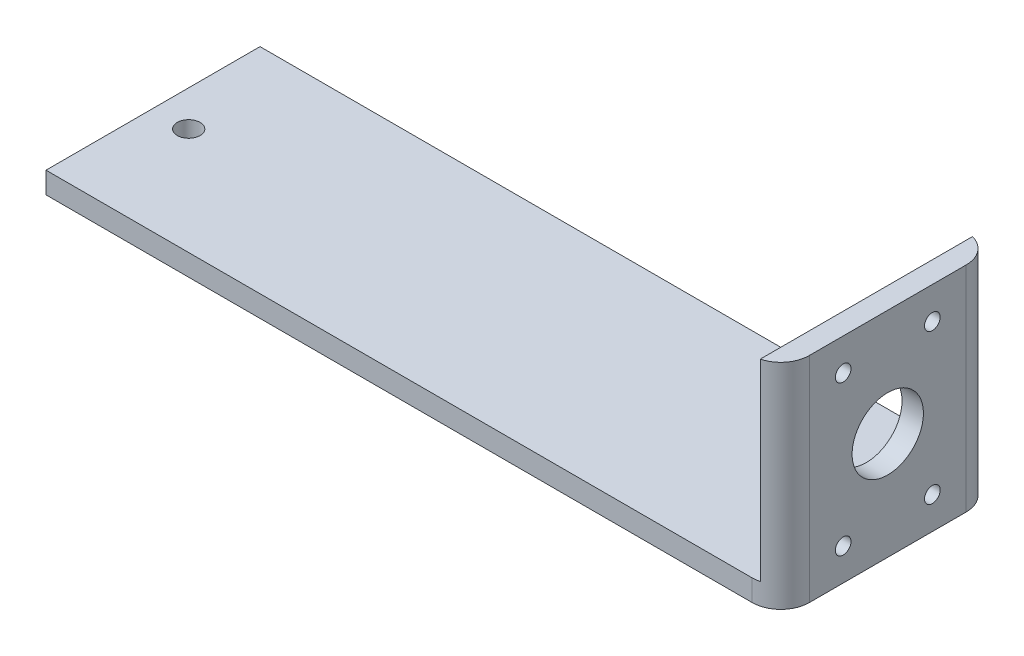
SolidWorks part; units mm, degrees
ref_plane "Front Plane" through (0, 0, 0) normal (0, 0, 1) x (1, 0, 0)
ref_plane "Top Plane" through (0, 0, 0) normal (0, 1, 0) x (1, 0, 0)
ref_plane "Right Plane" through (0, 0, 0) normal (1, 0, 0) x (0, 0, -1)
sketch "Sketch1" plane through (0, 0, 0) normal (0, 1, 0) x (1, 0, 0)
  line L1 (-50, 15) -> (50, 15)
  line L2 (-50, 15) -> (-50, -15)
  line L3 (-50, -15) -> (50, -15)
  line L4 (50, 15) -> (50, -15)
  line L5 (-50, 15) -> (50, -15) construction
  line L6 (-50, -15) -> (50, 15) construction
  point P0 (0, 0)
  dimension "D1" = 100
  dimension "D2" = 30
extrude "Boss-Extrude1" add sketch "Sketch1" along normal blind 3
sketch "Sketch2" plane through (0, 3, 0) normal (0, 1, 0) x (1, 0, 0)
  line L0 (0, -1.65) -> (0, 1.65) construction
  circle A0 centre (45, 0) radius 1.6
  circle A1 centre (-45, 0) radius 1.6
  dimension "D1" = 45
  dimension "D2" = 3.2
extrude "Cut-Extrude1" cut sketch "Sketch2" against normal through all
sketch "Sketch5" plane through (50, 0, 0) normal (1, 0, 0) x (0, 0, -1)
  line L1 (-15, 0) -> (15, 0)
  line L2 (-15, 0) -> (-15, 30)
  line L3 (-15, 30) -> (15, 30)
  line L4 (15, 0) -> (15, 30)
  dimension "D1" = 30
  dimension "D2" = 30
extrude "Boss-Extrude2" add sketch "Sketch5" along normal blind 3
sketch "Sketch6" plane through (53, 0, 0) normal (1, 0, 0) x (0, 0, -1)
  line L0 (-15, 30) -> (-6.25, 21.25) construction
  line L1 (0, 16.5) -> (0, -16.5) construction
  line L2 (-6.25, 25.5) -> (-5.15, 25.5)
  line L3 (-6.25, 25.5) -> (-6.25, 21.25)
  line L4 (-6.25, 4.5) -> (-5.15, 4.5)
  line L5 (6.25, 25.5) -> (6.25, 24.4)
  line L6 (-6.25, 25.5) -> (-5.6874, 24.5548) construction
  line L7 (-6.25, 4.5) -> (-5.6874, 5.4452) construction
  line L8 (-15, 15) -> (6.25, 15) construction
  line L9 (-15, 30) -> (-15, 0) construction
  line L11 (-6.25, 5.6) -> (-6.25, 4.5)
  line L13 (5.6874, 5.4452) -> (6.25, 4.5) construction
  line L14 (5.15, 25.5) -> (6.25, 25.5)
  line L15 (5.6874, 24.5548) -> (6.25, 25.5) construction
  line L16 (6.25, 5.6) -> (6.25, 4.5)
  line L17 (5.15, 4.5) -> (6.25, 4.5)
  circle A0 centre (-6.25, 25.5) radius 1.1
  circle A1 centre (6.25, 25.5) radius 1.1
  circle A2 centre (6.25, 4.5) radius 1.1
  circle A3 centre (-6.25, 4.5) radius 1.1
  point P6 (0, 15)
  dimension "D1" = 21
  dimension "D3" = 2.2
  dimension "D2" = 12.5
extrude "Cut-Extrude2" cut sketch "Sketch6" against normal through all contours A0 | A1 | A3 | A2
sketch "Sketch7" plane through (53, 0, 0) normal (1, 0, 0) x (0, 0, -1)
  circle A0 centre (0, 15) radius 5
  dimension "D1" = 10
extrude "Cut-Extrude3" cut sketch "Sketch7" against normal through all
fillet "Fillet1" radius 4 2 edges at (53, 15, -15) (53, 15, 15)
